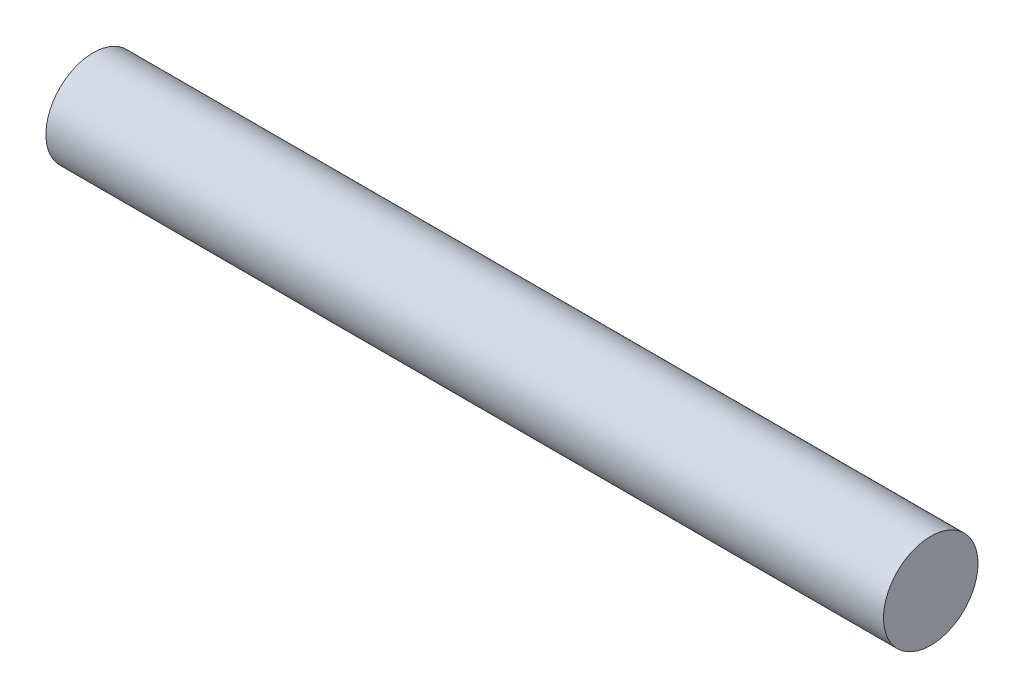
SolidWorks part; units mm, degrees
material "AISI 1020"
ref_plane "Front Plane" through (0, 0, 0) normal (0, 0, 1) x (1, 0, 0)
ref_plane "Top Plane" through (0, 0, 0) normal (0, 1, 0) x (1, 0, 0)
ref_plane "Right Plane" through (0, 0, 0) normal (1, 0, 0) x (0, 0, -1)
sketch "Sketch1" plane through (0, 0, 0) normal (1, 0, 0) x (0, 0, -1)
  circle A0 centre (0, 0) radius 5
  dimension "D1" = 10
extrude "Boss-Extrude1" add sketch "Sketch1" along normal blind 88.6
